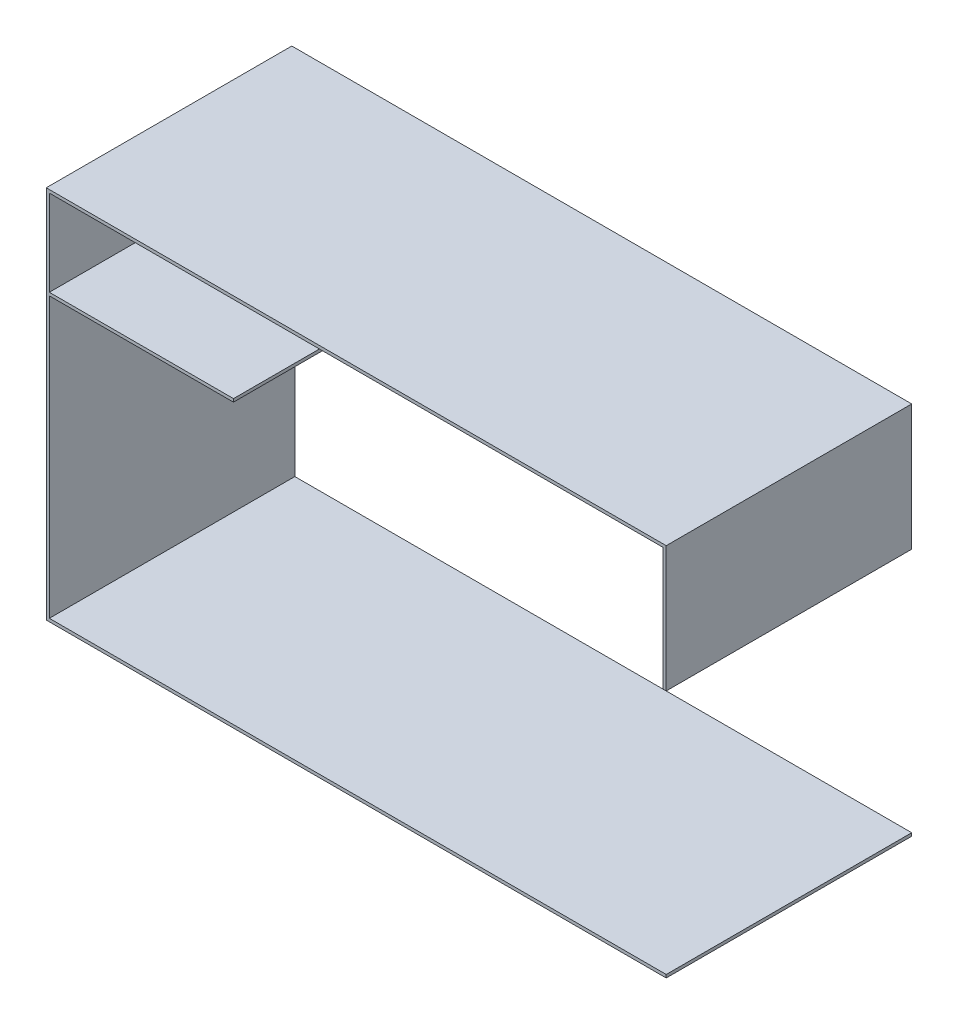
SolidWorks part; units mm, degrees
ref_plane "Front Plane" through (0, 0, 0) normal (0, 0, 1) x (1, 0, 0)
ref_plane "Top Plane" through (0, 0, 0) normal (0, 1, 0) x (1, 0, 0)
ref_plane "Right Plane" through (0, 0, 0) normal (1, 0, 0) x (0, 0, -1)
sketch "Sketch1" plane through (0, 0, 0) normal (0, 0, 1) x (1, 0, 0)
  line L0 (-2500, 800) -> (-1000, 800)
  line L1 (2500, -1500) -> (-2500, -1500)
  line L3 (2500, 1500) -> (-2500, 1500)
  line L4 (-2500, -1500) -> (-2500, 775)
  line L5 (2500, 1500) -> (2500, 500)
  line L6 (2500, 500) -> (2525, 500)
  line L7 (2525, 500) -> (2525, 1525)
  line L8 (2525, 1525) -> (-2525, 1525)
  line L9 (-2525, 1525) -> (-2525, -1525)
  line L10 (-2525, -1525) -> (2525, -1525)
  line L11 (2525, -1525) -> (2525, -1500)
  line L12 (2525, -1500) -> (2500, -1500)
  line L13 (-1000, 800) -> (-1000, 775)
  line L14 (-1000, 775) -> (-2500, 775)
  line L15 (-2500, 800) -> (-2500, 1500)
  point P0 (0, 0)
  point P9 (-2500, 0)
  point P10 (0, 1500)
  point P12 (2500, 500)
  dimension "D1" = 3000
  dimension "D2" = 5000
  dimension "D3" = 2300
  dimension "D4" = 1500
  dimension "D5" = 1500
  dimension "D6" = 1000
  dimension "D7" = 25
  dimension "D8" = 25
  dimension "D9" = 25
  dimension "D10" = 25
  dimension "D11" = 25
  dimension "D12" = 25
extrude "Boss-Extrude1" add sketch "Sketch1" along normal blind 2000 contours L4 L14 L13 L0 L15 L3 L5 L6 L7 L8 L9 L10 L11 L12 L1
ref_plane "Plane1" through (0, 0, 1000) normal (0, 0, 1) x (1, 0, 0)
sketch "Sketch2" plane through (0, 0, 1000) normal (0, 0, 1) x (1, 0, 0)
  line L0 (2403.6355, -1499.9666) -> (2406.9728, -999.9777)
  line L1 (2525, -1500) -> (-2500, -1500) construction
  line L2 (4458.362, -1405.0403) -> (4858.9216, -1405.0403)
  line L3 (4458.362, -1405.0403) -> (4458.362, -1594.9597)
  line L4 (4458.362, -1594.9597) -> (4858.9216, -1594.9597)
  line L5 (4858.9216, -1405.0403) -> (4858.9216, -1594.9597)
  line L6 (4458.362, -1405.0403) -> (4858.9216, -1594.9597) construction
  line L7 (4458.362, -1594.9597) -> (4858.9216, -1405.0403) construction
  line L8 (2403.6355, -1499.9666) -> (2406.9728, -999.9777)
  line L9 (2416.9846, 499.9889) -> (2413.6473, 0)
  line L10 (2413.6473, 0) -> (2416.9846, 499.9889)
  line L11 (2406.9728, -999.9777) -> (2413.6473, 0)
  line L12 (2413.6473, 0) -> (4658.6418, -1500)
  line L13 (600, -300) -> (2406.9728, -999.9777)
  line L14 (705.1575, -227.3452) -> (494.8425, -227.3452)
  line L15 (705.1575, -227.3452) -> (705.1575, -372.6548)
  line L16 (705.1575, -372.6548) -> (494.8425, -372.6548)
  line L17 (494.8425, -227.3452) -> (494.8425, -372.6548)
  line L18 (705.1575, -227.3452) -> (494.8425, -372.6548) construction
  line L19 (705.1575, -372.6548) -> (494.8425, -227.3452) construction
  point P4 (2406.9728, -999.9777)
  point P5 (4658.6418, -1500)
  point P11 (2413.6473, 0)
  point P20 (600, -300)
  dimension "D1" = 2000
  dimension "D2" = 1000
  dimension "D3" = 2700
  dimension "D4" = 600
  dimension "D5" = 300
  dimension "D6" = 1937.8131
sketch "Sketch3" plane through (0, 0, 1000) normal (0, 0, 1) x (1, 0, 0)
  line L0 (2493.7378, 500) -> (2493.7378, -1500)
  line L1 (2525, -1500) -> (-2500, -1500) construction
  line L14 (-2500, 818.0081) -> (-500, 818.0081)
  line L15 (-1800, 818.0081) -> (-2500, 818.0081)
  line L16 (-2500, 800) -> (-2500, 1500) construction
  line L17 (-1800, 818.0081) -> (2493.7378, -250) construction
  line L18 (-1000, 818.0081) -> (2493.7378, -1000) construction
  line L19 (346.8689, 284.004) -> (-96.8775, -1500) construction
  line L20 (-690.9379, -2854.0859) -> (746.8689, -90.996) construction
  point P20 (-1800, 818.0081)
  point P21 (-1000, 818.0081)
  point P25 (2493.7378, -250)
  point P27 (2493.7378, -1000)
  point P32 (346.8689, 284.004)
  point P33 (746.8689, -90.996)
  dimension "D2" = 2000
  dimension "D3" = 2000
  dimension "D4" = 500
  dimension "D5" = 800
  dimension "D6" = 500
  dimension "D7" = 750
sketch "Sketch5" plane through (0, 0, 1000) normal (0, 0, 1) x (1, 0, 0)
  line L0 (-646.4685, -2768.6273) -> (1393.3289, 1151.3318) construction
  line L1 (-690.9379, -2854.0859) -> (746.8689, -90.996) construction
  line L2 (346.8689, 284.004) -> (-96.8775, -1500) construction
  line L3 (435.4494, -847.6768) -> (478.7507, -772.6768)
  line L4 (478.7507, -772.6768) -> (435.4494, -697.6768)
  line L5 (435.4494, -697.6768) -> (348.8469, -697.6768)
  line L6 (348.8469, -697.6768) -> (305.5456, -772.6768)
  line L7 (305.5456, -772.6768) -> (348.8469, -847.6768)
  line L8 (348.8469, -847.6768) -> (435.4494, -847.6768)
  line L9 (-53.5763, -1575) -> (-10.275, -1500)
  line L10 (-10.275, -1500) -> (-53.5763, -1425)
  line L11 (-53.5763, -1425) -> (-140.1788, -1425)
  line L12 (-140.1788, -1425) -> (-183.4801, -1500)
  line L13 (-183.4801, -1500) -> (-140.1788, -1575)
  line L14 (-140.1788, -1575) -> (-53.5763, -1575)
  line L15 (2525, -1500) -> (-2500, -1500) construction
  line L16 (2493.7378, 500) -> (2493.7378, -1500) construction
  line L17 (-2500, 818.0081) -> (-500, 818.0081) construction
  line L18 (-1800, 818.0081) -> (-2500, 818.0081) construction
  line L19 (2493.7378, 500) -> (2493.7378, -1500)
  line L20 (-2500, 818.0081) -> (-500, 818.0081)
  line L21 (-1800, 818.0081) -> (-2500, 818.0081)
  line L22 (2852.9649, 133.1857) -> (2304.8257, -1790.234)
  line L23 (392.1481, -772.6768) -> (2436.3791, -1328.6132)
  line L24 (2641.9313, -607.3309) -> (-96.8775, -1500)
  circle A0 centre (392.1481, -772.6768) radius 75 construction
  circle A1 centre (-96.8775, -1500) radius 75 construction
  point P6 (2641.9313, -607.3309)
  point P33 (2436.3791, -1328.6132)
  dimension "D1" = 150
  dimension "D2" = 480
  dimension "D3" = 750
  dimension "D4" = 2000
  dimension "D5" = 2880.6132
  dimension "D6" = 2118.4772
sketch "Sketch8" plane through (0, 0, 0) normal (0, 0, 1) x (1, 0, 0)
  line L0 (-2500, 800) -> (-1000, 800) construction
  line L1 (-2500, 800) -> (-2500, 1500) construction
  line L2 (2525, -1500) -> (-2500, -1500) construction
  line L3 (2500, 909.3706) -> (2500, -1500) construction
  line L4 (-1800, 800) -> (2500, -200) construction
  line L5 (-1200, 800) -> (2500, -800) construction
  line L6 (-285.0821, -2430.853) -> (350, 300) construction
  line L7 (-543.2449, -2759.3788) -> (650, 0) construction
  line L21 (2472.2368, 525.6267) -> (2513.8177, -1473.941)
  line L22 (2500, 1500) -> (2500, 500) construction
  line L23 (282.4324, -850) -> (2499.2644, -774.0923)
  line L24 (-68.6047, -1500) -> (2486.7901, -174.222)
  line L25 (-500, 800) -> (-2500, 800) construction
  line L26 (-2500, -1500) -> (-2500, 775) construction
  line L27 (-2500, 100) -> (-2500, -100)
  line L40 (-2500, 0) -> (-1092.535, 188.261)
  line L45 (1107.5274, -889.8046) -> (-1092.535, 188.261)
  arc A0 (2500, -200) -> (-1800, 800) centre (-68.6047, -1500) ccw
  arc A5 (2500, -800) -> (-1200, 800) centre (282.4324, -850) ccw
  arc A6 (-2500, -100) -> (-2500, 100) centre (-2500, 0) ccw
  point P0 (-1800, 800)
  point P1 (-1200, 800)
  point P4 (2500, -200)
  point P5 (2500, -800)
  point P23 (-1160.4829, 471.2684)
  point P24 (2515.0271, -799.8377)
  point P25 (650, 0)
  point P26 (2486.7901, -174.222)
  point P28 (350, 300)
  point P31 (2500, -200)
  point P32 (2499.2644, -774.0923)
  point P37 (-2500, -100)
  point P38 (-2500, 100)
  point P42 (0, 0)
  point P43 (-491.3002, 1368.1312)
  point P45 (-1989.7293, 1350.0476)
  point P46 (-1828.8583, 1249.0374)
  point P47 (-1158.0261, 464.2262)
  point P48 (1089.5872, -850)
  point P50 (2292.6164, 146.9259)
  point P53 (2499.2644, -774.0923)
  point P65 (-500, 800)
  dimension "D11" = 100
  dimension "D1" = 700
  dimension "D3" = 700
  dimension "D4" = 700
  dimension "D2" = 2000
  dimension "D9" = 700
  dimension "D6" = 2000
  dimension "D5" = 650
  dimension "D7" = 700
  dimension "D8" = 700
  dimension "D10" = 1500
  dimension "D13" = 1420
  dimension "D17" = 2450
  dimension "D18" = 1325
  dimension "D12" = 68.6047
equation "\"top\"= 700"
equation "\"bottom\"= 700"
equation "\"D1@Sketch8\"=\"top\""
equation "\"D3@Sketch8\"=\"top\""
equation "\"D4@Sketch8\"=\"bottom\""
equation "\"D9@Sketch8\"=\"bottom\""
equation "\"D7@Sketch8\"=\"bottom\""
equation "\"D8@Sketch8\"=\"top\""
equation "\"R\"= 100"
equation "\"l1\"= \"l2\" * 2.8076"
equation "\"l2\"= 1425"
equation "\"l3\"= \"l2\" * 1.7590"
equation "\"l4\"= \"l2\" * 0.9765"
